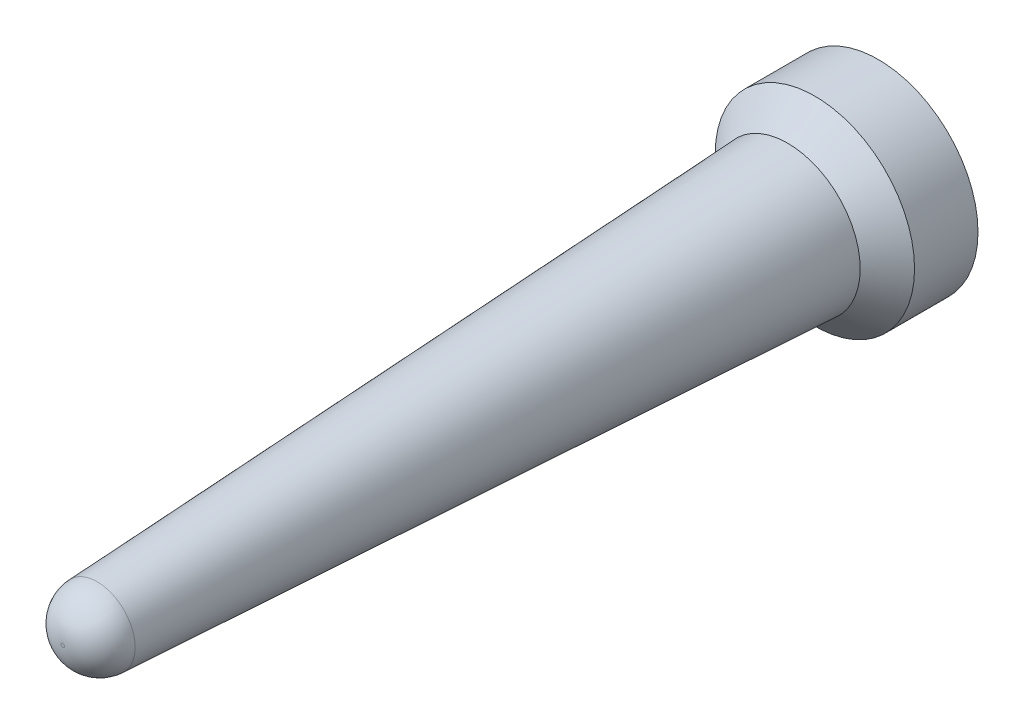
SolidWorks part; units mm, degrees
ref_plane "Front Plane" through (0, 0, 0) normal (0, 0, 1) x (1, 0, 0)
ref_plane "Top Plane" through (0, 0, 0) normal (0, 1, 0) x (1, 0, 0)
ref_plane "Right Plane" through (0, 0, 0) normal (1, 0, 0) x (0, 0, -1)
sketch "Sketch1" plane through (0, 0, 0) normal (0, 1, 0) x (1, 0, 0)
  line L0 (0, 0) -> (0.2794, 0)
  line L1 (0.2794, 0) -> (0.2794, -0.1778)
  line L2 (0.2794, -0.1778) -> (0.2032, -0.254)
  line L3 (0.2032, -0.254) -> (0.1064, -2.1895)
  line L4 (0.005, -2.286) -> (0, -2.286)
  line L5 (0, -2.286) -> (0, 0)
  line L6 (0.2032, -0.254) -> (0, -0.254) construction
  arc A0 (0.1064, -2.1895) -> (0.005, -2.286) centre (0.005, -2.1844) cw
  point P10 (0.1016, -2.286)
  dimension "D7" = 0.1016
  dimension "D1" = 0.1016
  dimension "D2" = 0.2032
  dimension "D3" = 2.032
  dimension "D4" = 2.286
  dimension "D5" = 135
  dimension "D6" = 0.2794
revolve "Revolve1" add sketch "Sketch1" angle 360 about L5
